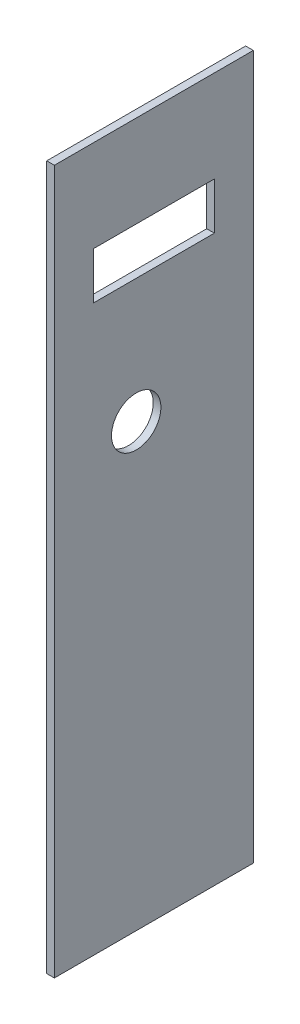
SolidWorks part; units mm, degrees
ref_plane "Front Plane" through (0, 0, 0) normal (0, 0, 1) x (1, 0, 0)
ref_plane "Top Plane" through (0, 0, 0) normal (0, 1, 0) x (1, 0, 0)
ref_plane "Right Plane" through (0, 0, 0) normal (1, 0, 0) x (0, 0, -1)
sketch "Sketch1" plane through (0, 0, 0) normal (1, 0, 0) x (0, 0, -1)
  line L1 (0, 0) -> (82.55, 0)
  line L2 (0, 0) -> (0, 292.1)
  line L3 (0, 292.1) -> (82.55, 292.1)
  line L4 (82.55, 0) -> (82.55, 292.1)
  dimension "D1" = 82.55
  dimension "D2" = 292.1
extrude "Boss-Extrude1" add sketch "Sketch1" along normal blind 3.175 contours L3 L4 L1 L2
sketch "Sketch2" plane through (0, 0, 0) normal (-1, 0, 0) x (0, 0, 1)
  line L0 (0, 292.1) -> (-82.55, 292.1) construction
  line L1 (-66.4, 234.5) -> (-16.15, 234.5)
  line L2 (-66.4, 234.5) -> (-66.4, 254)
  line L3 (-66.4, 254) -> (-16.15, 254)
  line L4 (-16.15, 234.5) -> (-16.15, 254)
  line L5 (0, 292.1) -> (-82.55, 292.1) construction
  point P7 (0, 0)
  point P8 (-41.275, 292.1)
  point P9 (-41.275, 254)
  dimension "D1" = 50.25
  dimension "D2" = 19.5
  dimension "D3" = 38.1
extrude "Cut-Extrude1" cut sketch "Sketch2" against normal up to next
ref_plane "Plane1" through (0, 0, -41.275) normal (0, 0, -1) x (-1, 0, 0)
sketch "Sketch4" plane through (0, 0, 0) normal (-1, 0, 0) x (0, 0, 1)
  circle A0 centre (-33.9635, 183.0375) radius 10.25
  dimension "D1" = 20.5
extrude "Cut-Extrude2" cut sketch "Sketch4" against normal up to next
